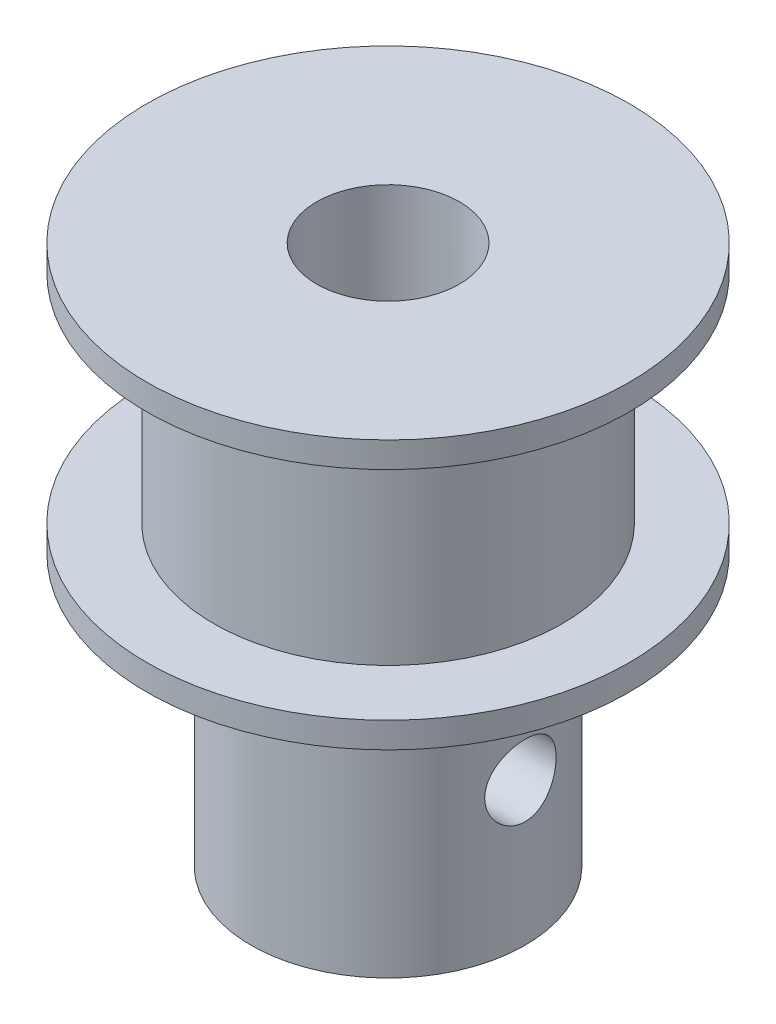
SolidWorks part; units mm, degrees
ref_plane "Alzado" through (0, 0, 0) normal (0, 0, 1) x (1, 0, 0)
ref_plane "Planta" through (0, 0, 0) normal (0, 1, 0) x (1, 0, 0)
ref_plane "Vista lateral" through (0, 0, 0) normal (1, 0, 0) x (0, 0, -1)
sketch "Croquis1" plane through (0, 0, 0) normal (0, 0, 1) x (1, 0, 0)
  line L0 (0, 0) -> (0, 36.7556) construction
  line L1 (8.45, 9.5) -> (4.8, 9.5)
  line L2 (4.8, 9.5) -> (4.8, 0)
  line L3 (2.5, 18.9) -> (8.45, 18.9)
  line L4 (8.45, 18.9) -> (8.45, 18)
  line L5 (8.45, 18) -> (6.1, 18)
  line L6 (6.1, 18) -> (6.1, 10.4)
  line L7 (6.1, 10.4) -> (8.45, 10.4)
  line L8 (8.45, 10.4) -> (8.45, 9.5)
  line L9 (4.8, 0) -> (2.5, 0)
  line L10 (2.5, 0) -> (2.5, 18.9)
  dimension "D1" = 0.9
  dimension "D2" = 0.9
  dimension "D3" = 18.9
  dimension "D4" = 5
  dimension "D5" = 12.2
  dimension "D6" = 16.9
  dimension "D7" = 16.9
  dimension "D8" = 9.6
  dimension "D11" = 7.6
revolve "Revolución1" add sketch "Croquis1" angle 360 about L0
sketch "Croquis2" plane through (0, 0, 0) normal (0, 0, 1) x (1, 0, 0)
  line L0 (-4.8, 0) -> (4.8, 0) construction
  circle A0 centre (0, 5) radius 1.25
  dimension "D1" = 5
  dimension "D2" = 2.5
extrude "Cortar-Extruir1" cut sketch "Croquis2" against normal up to next
pattern_circular "MatrizC1" count 2 over 90 about axis through (0, 0, 0) along (0, -1, 0) of "Cortar-Extruir1"
